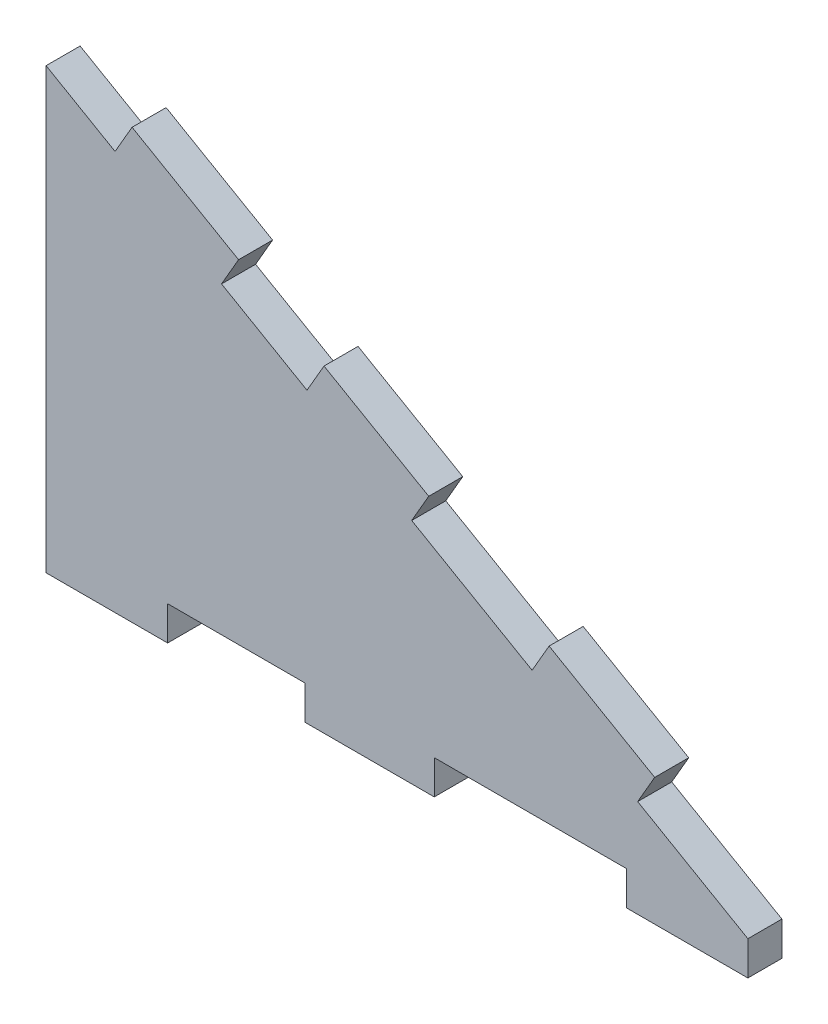
SolidWorks part; units mm, degrees
ref_plane "Front Plane" through (0, 0, 0) normal (0, 0, 1) x (1, 0, 0)
ref_plane "Top Plane" through (0, 0, 0) normal (0, 1, 0) x (1, 0, 0)
ref_plane "Right Plane" through (0, 0, 0) normal (1, 0, 0) x (0, 0, -1)
sketch "Sketch1" plane through (0, 0, 0) normal (0, 0, 1) x (1, 0, 0)
  line L1 (0, 0) -> (109.982, 0)
  line L2 (0, 0) -> (0, 63.5)
  line L3 (0, 63.5) -> (109.982, 63.5)
  line L4 (109.982, 0) -> (109.982, 63.5)
  dimension "D1" = 109.982
  dimension "D2" = 63.5
extrude "Boss-Extrude1" add sketch "Sketch1" along normal blind 5.334 contours L2 L1 L4 L3
sketch "Sketch2" plane through (0, 0, 5.334) normal (0, 0, 1) x (1, 0, 0)
  line L0 (0, 63.5) -> (109.982, 0)
  line L1 (0, 63.5) -> (109.982, 63.5)
  line L2 (109.982, 63.5) -> (109.982, 0)
extrude "Cut-Extrude1" cut sketch "Sketch2" against normal through all
sketch "Sketch7" plane through (0, 0, 0) normal (0, -1, 0) x (-1, 0, 0)
  line L0 (0, 0) -> (-109.982, 0) construction
  line L1 (0, -5.334) -> (-19.05, -5.334)
  line L2 (0, -5.334) -> (0, 0)
  line L3 (0, 0) -> (-19.05, 0)
  line L4 (-19.05, -5.334) -> (-19.05, 0)
  line L5 (0, -5.334) -> (-109.982, -5.334) construction
  line L6 (-40.5379, -5.334) -> (-60.8337, -5.334)
  line L7 (-40.5379, -5.334) -> (-40.5379, 0)
  line L8 (-40.5379, 0) -> (-60.8337, 0)
  line L9 (-60.8337, -5.334) -> (-60.8337, 0)
  line L11 (-109.982, -5.334) -> (-90.932, -5.334)
  line L12 (-109.982, -5.334) -> (-109.982, 0)
  line L13 (-109.982, 0) -> (-90.932, 0)
  line L14 (-90.932, -5.334) -> (-90.932, 0)
  dimension "D1" = 19.05
  dimension "D2" = 19.05
extrude "Boss-Extrude4" add sketch "Sketch7" along normal blind 5.334
sketch "Sketch9" plane through (27.4967, 47.6243, 0) normal (0.5, 0.866, 0) x (0.866, -0.5, 0)
  line L0 (-31.7507, -5.334) -> (95.2465, -5.334) construction
  line L1 (-19.27, -5.334) -> (0, -5.334)
  line L2 (-19.27, -5.334) -> (-19.27, 0)
  line L3 (-19.27, 0) -> (0, 0)
  line L4 (0, -5.334) -> (0, 0)
  line L5 (-31.7507, 0) -> (95.2465, 0) construction
  line L6 (15.4646, -5.334) -> (34.4108, -5.334)
  line L7 (15.4646, -5.334) -> (15.4646, 0)
  line L8 (15.4646, 0) -> (34.4108, 0)
  line L9 (34.4108, -5.334) -> (34.4108, 0)
  line L11 (56.1989, -5.334) -> (75.3029, -5.334)
  line L12 (56.1989, -5.334) -> (56.1989, 0)
  line L13 (56.1989, 0) -> (75.3029, 0)
  line L14 (75.3029, -5.334) -> (75.3029, 0)
extrude "Boss-Extrude6" add sketch "Sketch9" along normal blind 5.334
equation "\"D2@Sketch1\"=2.5in"
equation "\"D1@Sketch1\"=4.33in"
equation "\"Gmaterial\"=0.21"
equation "\"D1@Boss-Extrude1\"=\"Gmaterial\""
equation "\"D2@Sketch7\"=.75in"
equation "\"D1@Boss-Extrude4\"=\"Gmaterial\""
equation "\"D1@Boss-Extrude6\"= \"Gmaterial\""
